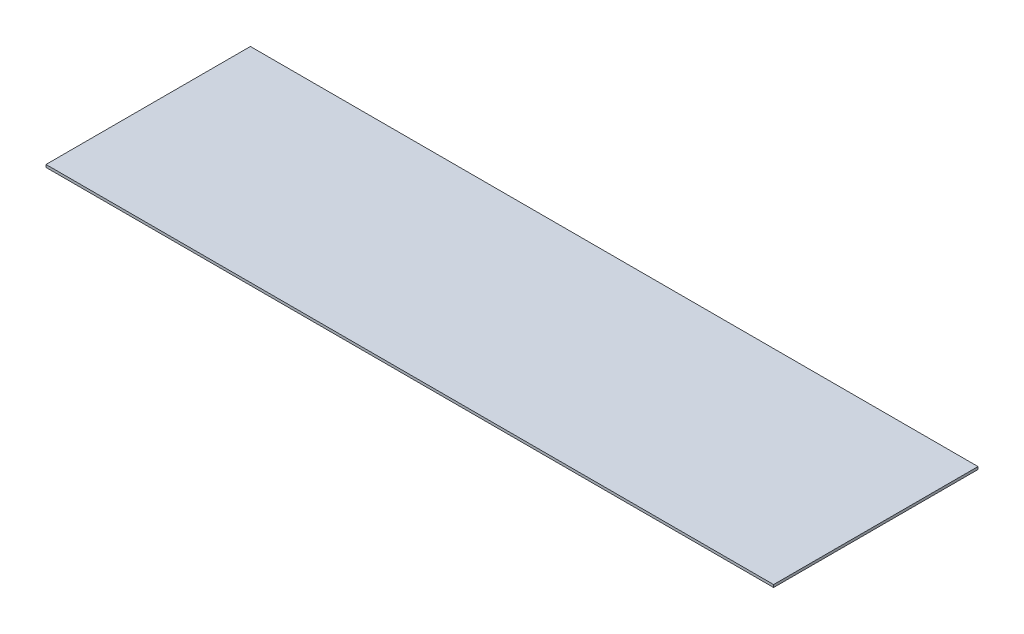
SolidWorks part; units mm, degrees
ref_plane "Front Plane" through (0, 0, 0) normal (0, 0, 1) x (1, 0, 0)
ref_plane "Top Plane" through (0, 0, 0) normal (0, 1, 0) x (1, 0, 0)
ref_plane "Right Plane" through (0, 0, 0) normal (1, 0, 0) x (0, 0, -1)
sketch "Sketch1" plane through (0, 0, 0) normal (0, 1, 0) x (1, 0, 0)
  line L1 (0, 0) -> (890, 0)
  line L2 (0, 0) -> (0, 250)
  line L3 (0, 250) -> (890, 250)
  line L4 (890, 0) -> (890, 250)
  dimension "D1" = 250
  dimension "D2" = 890
extrude "Boss-Extrude1" add sketch "Sketch1" along normal blind 3.175
